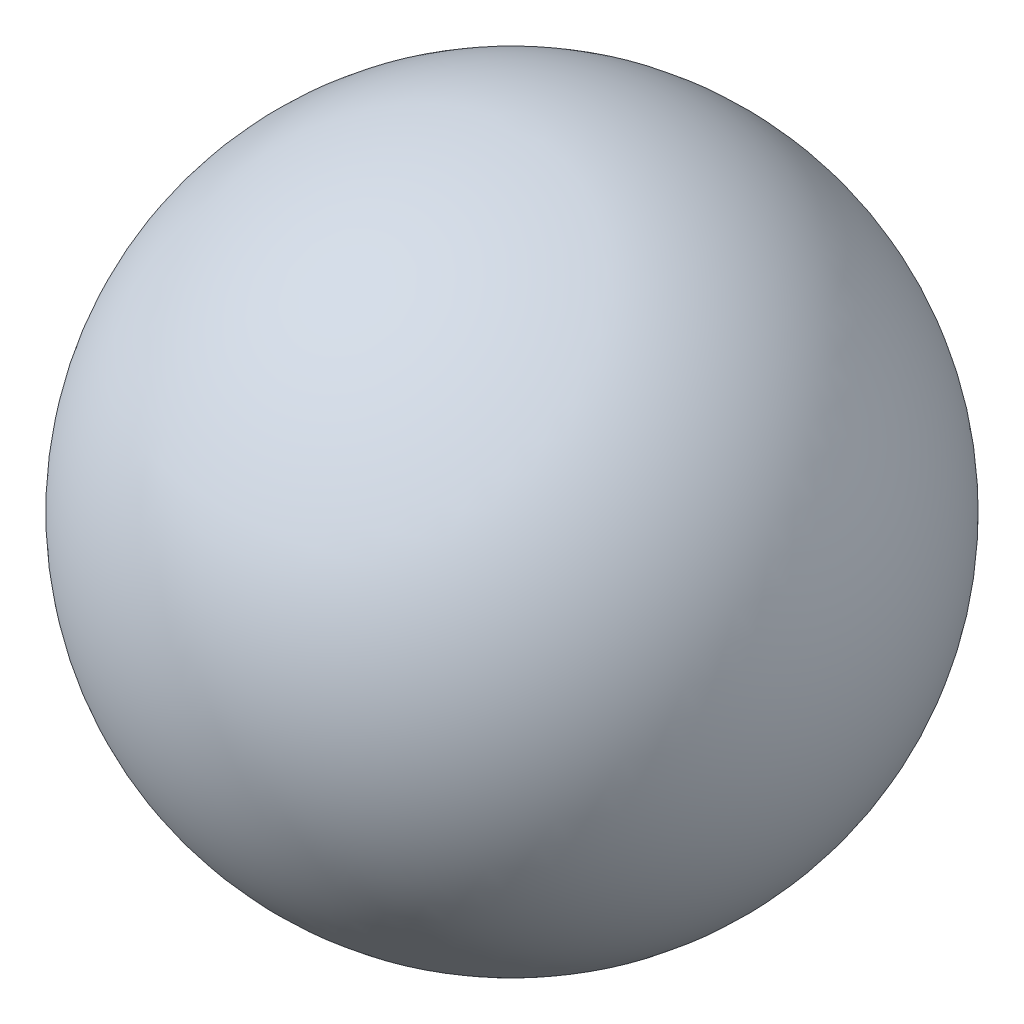
SolidWorks part; units mm, degrees
ref_plane "Front Plane" through (0, 0, 0) normal (1, 0, 0) x (0, 1, 0)
ref_plane "Top Plane" through (0, 0, 0) normal (0, 0, 1) x (0, 1, 0)
ref_plane "Right Plane" through (0, 0, 0) normal (0, 1, 0) x (-1, 0, 0)
sketch "Sketch2" plane through (0, 0, 0) normal (1, 0, 0) x (0, 1, 0)
  line L0 (0, -3.4925) -> (0, 3.4925) construction
  line L1 (0, 6.35) -> (0, 0)
  line L2 (0, 0) -> (-6.35, 0)
  arc A0 (0, 6.35) -> (-6.35, 0) centre (0, 0) ccw
  dimension "D1" = 6.35
ref_axis "Axis1" through (0, 0.3175, 0) along (0, -1, 0)
revolve "Revolve1" add sketch "Sketch2" angle 360 about axis through (0, 0.3175, 0) along (0, -1, 0)
mirror "Mirror1" about plane through (0, 0, 0) normal (0, 1, 0) of "Revolve1"
